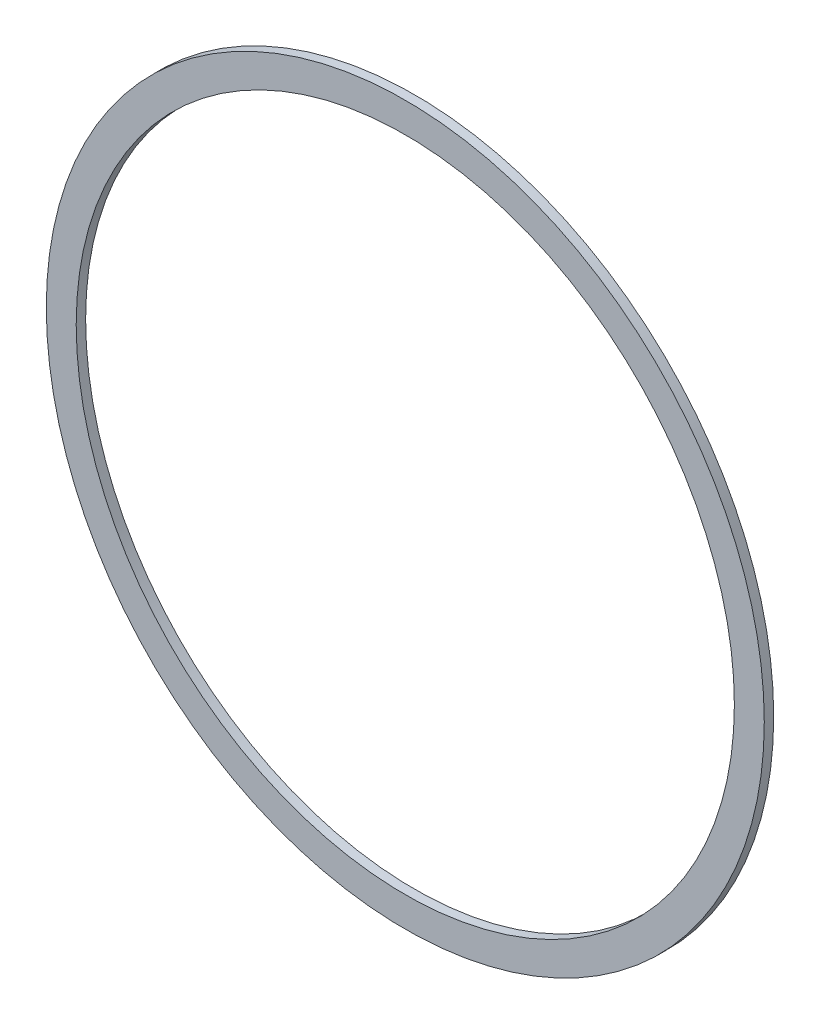
SolidWorks part; units mm, degrees
ref_plane "Front Plane" through (0, 0, 0) normal (0, 0, 1) x (1, 0, 0)
ref_plane "Top Plane" through (0, 0, 0) normal (0, 1, 0) x (1, 0, 0)
ref_plane "Right Plane" through (0, 0, 0) normal (1, 0, 0) x (0, 0, -1)
sketch "Sketch1" plane through (0, 0, 0) normal (0, 0, 1) x (1, 0, 0)
  circle A0 centre (0, 0) radius 76.2
  circle A1 centre (0, 0) radius 69.85
  dimension "D1" = 139.7
  dimension "D2" = 152.4
extrude "Boss-Extrude1" add sketch "Sketch1" along normal mid plane 2
